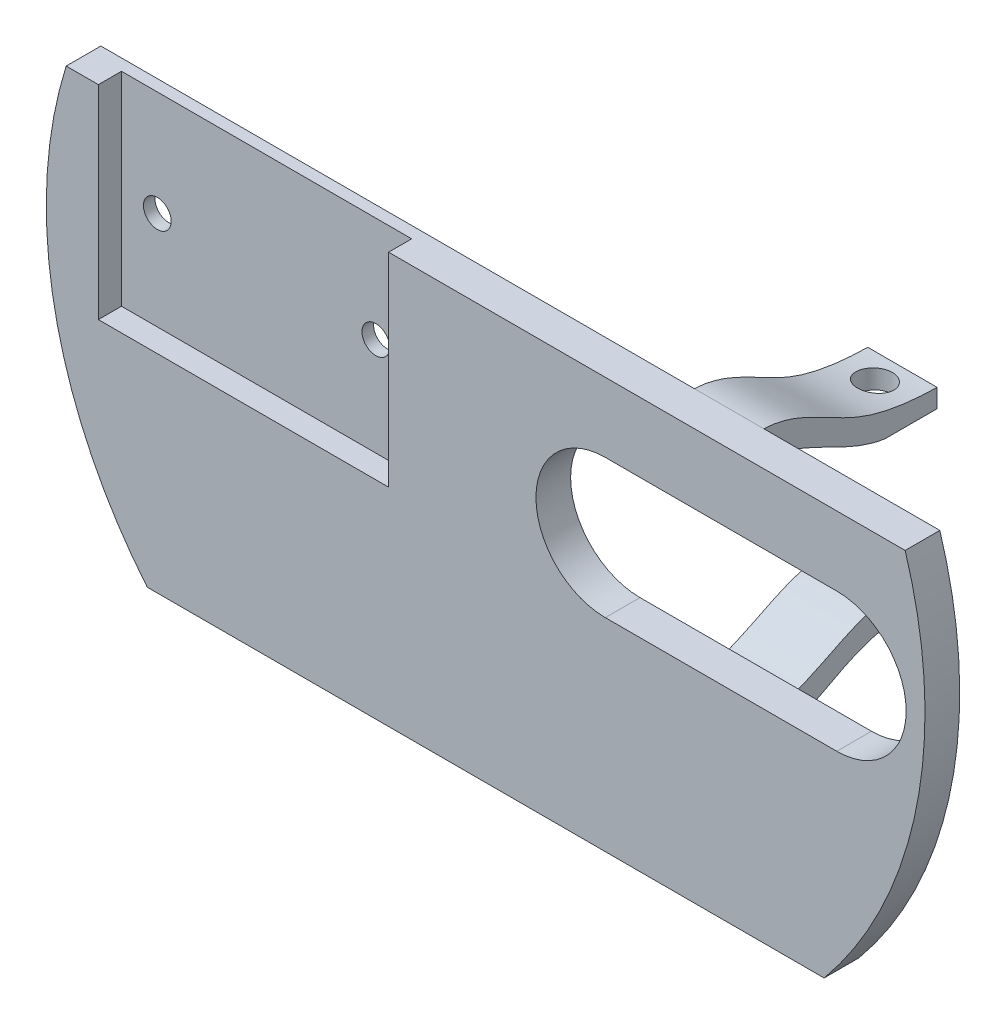
SolidWorks part; units mm, degrees
ref_plane "Front Plane" through (0, 0, 0) normal (0, 0, 1) x (1, 0, 0)
ref_plane "Top Plane" through (0, 0, 0) normal (0, 1, 0) x (1, 0, 0)
ref_plane "Right Plane" through (0, 0, 0) normal (1, 0, 0) x (0, 0, -1)
sketch "Sketch5" plane through (0, 0, 0) normal (0, 0, 1) x (1, 0, 0)
  line L1 (0, 22.6) -> (82.5, 22.6)
  line L2 (0, 22.6) -> (0, -12.931)
  line L3 (0, -12.931) -> (82.5, -12.931)
  line L4 (82.5, 22.6) -> (82.5, -12.931)
extrude "Boss-Extrude1" add sketch "Sketch5" along normal blind 3
sketch "Sketch7" plane through (0, 0, 3) normal (0, 0, 1) x (1, 0, 0)
  line L7 (7.7538, 28.6) -> (32.8538, 28.6)
  line L8 (7.7538, 28.6) -> (7.7538, 5)
  line L9 (7.7538, 5) -> (32.8538, 5)
  line L10 (32.8538, 28.6) -> (32.8538, 5)
  line L11 (82.5, 22.6) -> (0, 22.6) construction
  dimension "D2" = 6
  dimension "D3" = 23.6
  dimension "D4" = 25.1
sketch "Sketch8" plane through (0, 0, 3) normal (0, 0, 1) x (1, 0, 0)
  circle A0 centre (41.25, 11.3) radius 38
  circle A1 centre (41.25, 11.3) radius 53.7596
extrude "Cut-Extrude1" cut sketch "Sketch8" against normal blind 13
extrude "Cut-Extrude2" cut sketch "Sketch7" against normal blind 2
sketch "Sketch10" plane through (0, 0, 0) normal (0, 0, -1) x (-1, 0, 0)
  line L0 (-78.5316, 3.9459) -> (-44.7986, 10.6) construction
  line L1 (-44.7986, 10.6) -> (-56.3017, 10.6) construction
  line L2 (-56.3017, 10.6) -> (-56.3017, 22.6) construction
  line L3 (-56.3017, 10.6) -> (-56.3017, -1.4) construction
  line L4 (-56.3017, -1.4) -> (-62.3017, -1.4)
  line L5 (-56.3017, 22.6) -> (-62.3017, 22.6)
  line L6 (-77.531, 22.6) -> (-4.969, 22.6) construction
  line L7 (-62.3017, 22.6) -> (-62.3017, 16.6)
  line L8 (-62.3017, 16.6) -> (-56.3017, 16.6)
  line L9 (-56.3017, 16.6) -> (-56.3017, 22.6)
  line L10 (-62.3017, -1.4) -> (-62.3017, 4.6)
  line L11 (-62.3017, 4.6) -> (-56.3017, 4.6)
  line L12 (-56.3017, 4.6) -> (-56.3017, -1.4)
  arc A0 (-77.531, 22.6) -> (-70.5222, -12.931) centre (-41.25, 11.3) ccw construction
  point P14 (-62.3017, 19.6)
  point P16 (-62.3017, 1.6)
  dimension "D1" = 6
  dimension "D2" = 6
extrude "Boss-Extrude2" add sketch "Sketch10" along normal blind 15
sketch "Sketch11" plane through (56.3017, 0, 0) normal (-1, 0, 0) x (0, 0, 1)
  line L7 (4.9579, 22.6) -> (4.9579, -1.4)
  line L15 (4.9579, 10.6) -> (-2.4951, 10.6)
  line L22 (-15.6737, 18.1883) -> (-15.6737, 24.4509)
  line L23 (-15.6737, 24.4509) -> (0, 24.4509)
  line L24 (0, 24.4509) -> (0, 22.6)
  line L27 (0, 22.6) -> (0, 16.6) construction
  line L29 (0, 22.6) -> (3, 22.6) construction
  line L30 (-15, -1.4) -> (0, -1.4) construction
  line L31 (-15, 16.6) -> (0, 16.6) construction
  line L32 (-10.4846, 16.6) -> (-10.7083, 12.0151)
  line L33 (-10.7083, 12.0151) -> (0, 12.0151)
  line L34 (0, 22.6) -> (0, -12.931) construction
  line L35 (0, 12.0151) -> (0, 20.4249)
  line L36 (0, 9.1849) -> (0, 0.7751)
  line L37 (-10.7083, 9.1849) -> (0, 9.1849)
  line L38 (-10.4846, 4.6) -> (-10.7083, 9.1849)
  line L39 (0, -3.2509) -> (0, -1.4)
  line L40 (-15.6737, -3.2509) -> (0, -3.2509)
  line L41 (-15.6737, 3.0117) -> (-15.6737, -3.2509)
  spline S0 degree 3 poles (0, 22.6) (-3.1599, 22.4626) (-7.5478, 18.6903) (-13.2472, 18.201) (-15.6737, 18.1883) knots 0 0 0 0 0.549889 1 1 1 1
  spline S1 degree 3 poles (0, 20.4249) (-1.8374, 20.1919) (-5.2669, 18.6651) (-8.5557, 16.8819) (-10.4846, 16.6) knots 0 0 0 0 0.489528 1 1 1 1
  spline S2 degree 3 poles (0, 0.7751) (-1.8374, 1.0081) (-5.2669, 2.5349) (-8.5557, 4.3181) (-10.4846, 4.6) knots 0 0 0 0 0.489528 1 1 1 1
  spline S3 degree 3 poles (0, -1.4) (-3.1599, -1.2626) (-7.5478, 2.5097) (-13.2472, 2.999) (-15.6737, 3.0117) knots 0 0 0 0 0.549889 1 1 1 1
extrude "Cut-Extrude3" cut sketch "Sketch11" against normal blind 12
sketch "Sketch14" plane through (0, 0, 0) normal (0, 0, -1) x (-1, 0, 0)
  line L0 (-66.5148, 22.6) -> (-66.5148, -1.4) construction
  line L1 (-71.6183, 10.6) -> (-51.5982, 10.6) construction
  line L2 (-71.6183, 16.6) -> (-51.5982, 16.6)
  line L3 (-71.6183, 4.6) -> (-51.5982, 4.6)
  arc A0 (-71.6183, 16.6) -> (-71.6183, 4.6) centre (-71.6183, 10.6) ccw
  arc A1 (-51.5982, 4.6) -> (-51.5982, 16.6) centre (-51.5982, 10.6) ccw
  point P6 (-61.6083, 10.6)
  point P11 (-66.5148, 10.6)
extrude "Cut-Extrude4" cut sketch "Sketch14" against normal blind 12
sketch "Sketch15" plane through (0, 16.6, 0) normal (0, -1, 0) x (-1, 0, 0)
  circle A0 centre (-59.2661, 12.6507) radius 1.5
extrude "Cut-Extrude5" cut sketch "Sketch15" along normal blind 17 and the other way blind 12
sketch "Sketch16" plane through (0, 0, 1) normal (0, 0, 1) x (1, 0, 0)
  line L0 (7.7538, 13.5) -> (10.8538, 13.5)
  line L1 (7.7538, 22.6) -> (7.7538, 5) construction
  line L2 (10.8538, 13.5) -> (10.8538, 5)
  line L3 (7.7538, 5) -> (32.8538, 5) construction
  line L4 (20.3038, 5) -> (20.3038, 17.6432)
  circle A0 centre (10.8538, 13.5) radius 1.2
  circle A1 centre (29.7538, 13.5) radius 1.2
extrude "Cut-Extrude6" cut sketch "Sketch16" against normal blind 10 contours L2 A0 L0 | L0 A0 L2 | A1
sketch "Sketch17" plane through (0, 0, 3) normal (0, 0, 1) x (1, 0, 0)
  line L0 (20.3038, 5) -> (20.3038, 21.2463)
  line L1 (7.7538, 5) -> (32.8538, 5) construction
